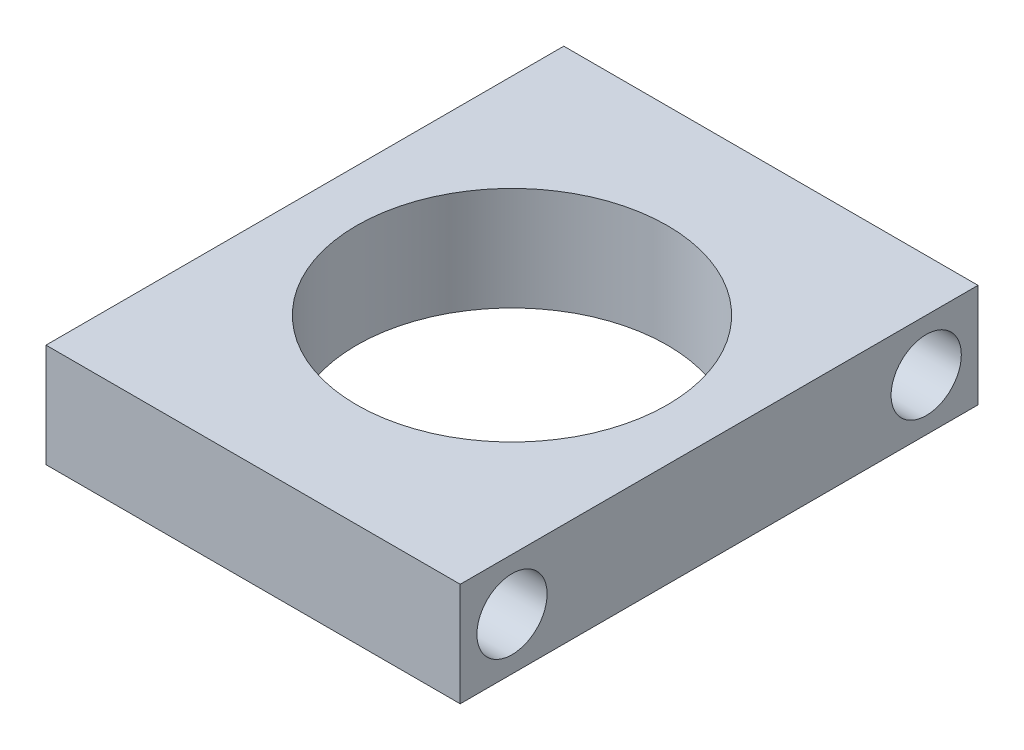
SolidWorks part; units mm, degrees
ref_plane "Front Plane" through (0, 0, 0) normal (0, 0, 1) x (1, 0, 0)
ref_plane "Top Plane" through (0, 0, 0) normal (0, 1, 0) x (1, 0, 0)
ref_plane "Right Plane" through (0, 0, 0) normal (1, 0, 0) x (0, 0, -1)
sketch "Sketch1" plane through (0, 0, 0) normal (0, 1, 0) x (1, 0, 0)
  line L1 (-25.4, 15.875) -> (0, 15.875)
  line L2 (-25.4, 15.875) -> (-25.4, -15.875)
  line L3 (-25.4, -15.875) -> (0, -15.875)
  line L4 (0, 15.875) -> (0, -15.875)
  dimension "D1" = 31.75
  dimension "D2" = 25.4
extrude "Boss-Extrude1" add sketch "Sketch1" against normal mid plane 6.35
sketch "Sketch3" plane through (0, 0, 0) normal (1, 0, 0) x (0, 0, -1)
  line L0 (17.4625, 0) -> (-17.4625, 0) construction
  circle A0 centre (-12.7, 0) radius 2.1526
  circle A2 centre (12.7, 0) radius 2.1526
  point P2 (0, 0)
  point P3 (0, 0)
  point P6 (0, 0)
  point P7 (0, 0)
  point P8 (0, 0)
  point P11 (0, 0)
  point P12 (-12.7, 0)
  point P15 (18.6213, -3.6088)
  dimension "D1" = 12.7
  dimension "D2" = 12.7
  dimension "D3" = 4.3053
extrude "Cut-Extrude1" cut sketch "Sketch3" against normal through all
sketch "Sketch4" plane through (0, 3.175, 0) normal (0, 1, 0) x (1, 0, 0)
  line L0 (-3.4925, 0) -> (3.4925, 0) construction
  line L1 (0, -15.875) -> (0, 15.875) construction
  circle A0 centre (-12.7, 0) radius 9.525
  point P2 (0, 0)
  dimension "D1" = 19.05
  dimension "D2" = 12.7
extrude "Cut-Extrude2" cut sketch "Sketch4" against normal through all contours A0
